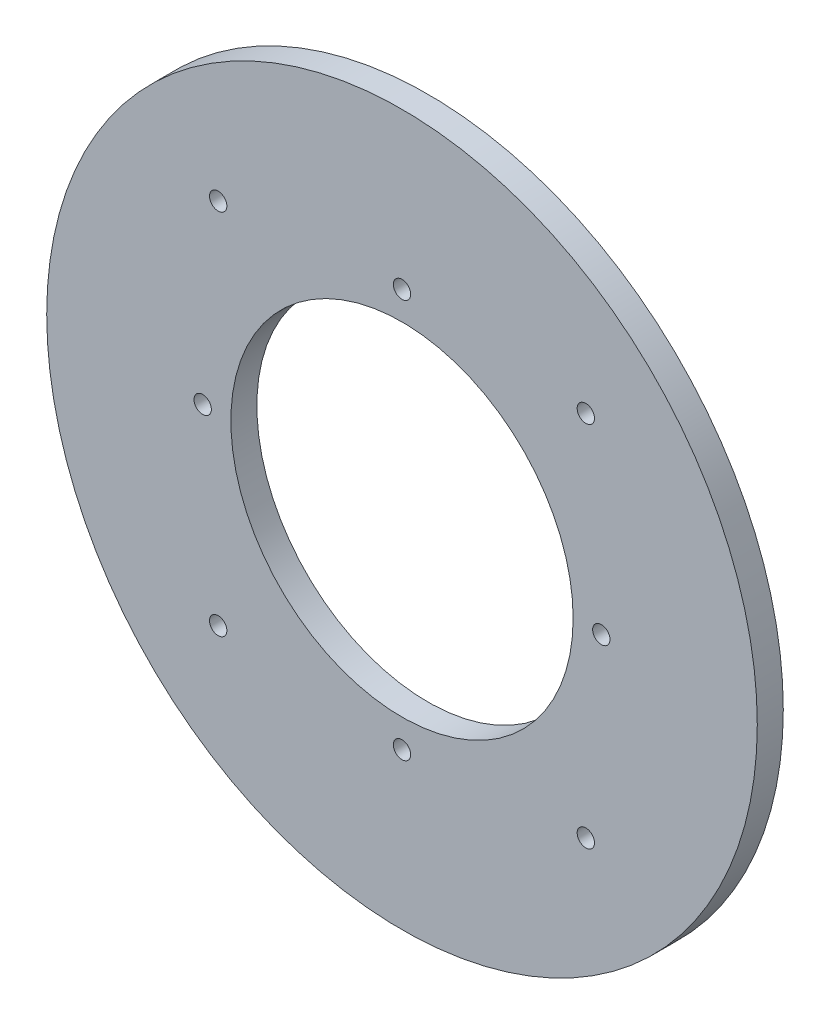
SolidWorks part; units mm, degrees
ref_plane "Front Plane" through (0, 0, 0) normal (0, 0, 1) x (1, 0, 0)
ref_plane "Top Plane" through (0, 0, 0) normal (0, 1, 0) x (1, 0, 0)
ref_plane "Right Plane" through (0, 0, 0) normal (1, 0, 0) x (0, 0, -1)
sketch "Sketch1" plane through (0, 0, 0) normal (0, 0, 1) x (1, 0, 0)
  circle A2 centre (0, 0) radius 39.5
  circle A3 centre (0, 0) radius 82
  point P19 (2, -2)
  dimension "D1" = 79
  dimension "D4" = 164
extrude "Boss-Extrude1" add sketch "Sketch1" along normal blind 6
sketch "Sketch2" plane through (0, 0, 6) normal (0, 0, 1) x (1, 0, 0)
  line L0 (0, 0) -> (82, 0) construction
  line L1 (0, 0) -> (57.9828, 57.9828) construction
  circle A0 centre (0, 0) radius 82 construction
  circle A1 centre (42.4264, 42.4264) radius 2
  dimension "D1" = 4
  dimension "D2" = 60
extrude "Cut-Extrude1" cut sketch "Sketch2" against normal blind 10 contours A1
pattern_circular "CirPattern1" count 4 every 90 about axis through (0, 0, 0) along (0, 0, 1) of "Cut-Extrude1"
sketch "Sketch3" plane through (0, 0, 6) normal (0, 0, 1) x (1, 0, 0)
  circle A0 centre (0, 46) radius 2
  circle A1 centre (46, 0) radius 2
  circle A2 centre (0, -46) radius 2
  circle A3 centre (-46, 0) radius 2
  point P12 (0, 0)
  dimension "D1" = 4
  dimension "D2" = 46
  dimension "D3" = 4
extrude "Cut-Extrude2" cut sketch "Sketch3" against normal blind 10
